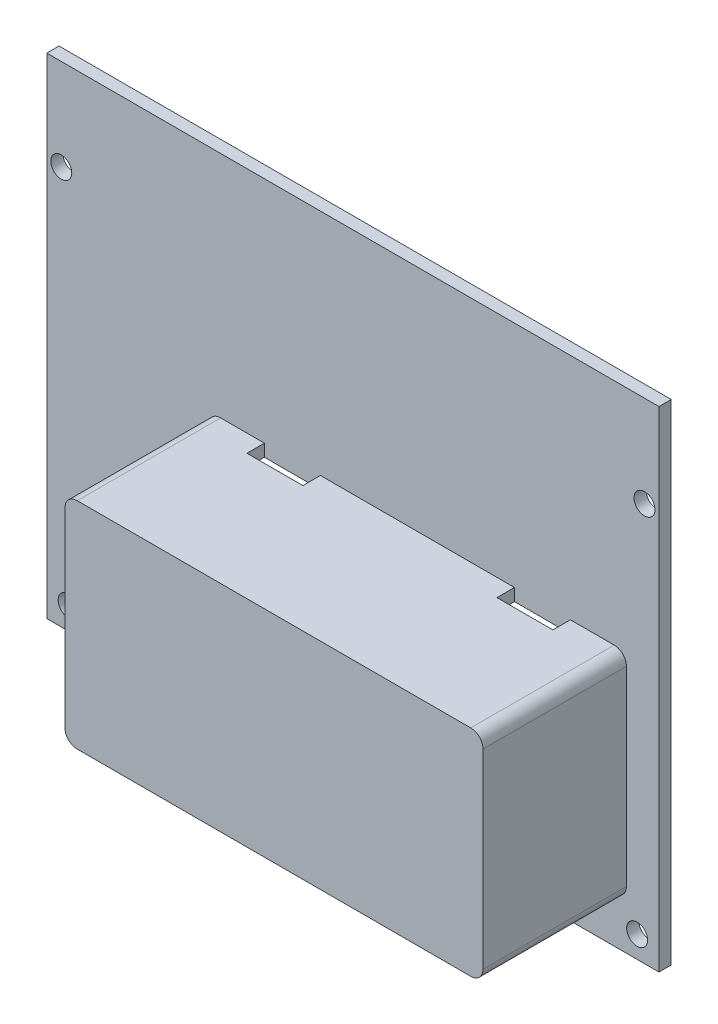
SolidWorks part; units mm, degrees
ref_plane "Front Plane" through (0, 0, 0) normal (0, 0, 1) x (1, 0, 0)
ref_plane "Top Plane" through (0, 0, 0) normal (0, 1, 0) x (1, 0, 0)
ref_plane "Right Plane" through (0, 0, 0) normal (1, 0, 0) x (0, 0, -1)
sketch "Sketch1" plane through (0, 0, 0) normal (0, 0, 1) x (1, 0, 0)
  line L1 (-44.45, 35.56) -> (44.45, 35.56)
  line L2 (-44.45, 35.56) -> (-44.45, -35.56)
  line L3 (-44.45, -35.56) -> (44.45, -35.56)
  line L4 (44.45, 35.56) -> (44.45, -35.56)
  line L5 (-44.45, 35.56) -> (44.45, -35.56) construction
  line L6 (-44.45, -35.56) -> (44.45, 35.56) construction
  point P0 (0, 0)
  dimension "D1" = 71.12
  dimension "D2" = 88.9
extrude "Boss-Extrude1" add sketch "Sketch1" along normal blind 1.778
sketch "Sketch2" plane through (0, 0, 0) normal (0, 0, -1) x (-1, 0, 0)
  circle A0 centre (-42.345, 22.2783) radius 1.524
  circle A1 centre (42.345, 22.2783) radius 1.524
  circle A2 centre (41.275, -32.385) radius 1.524
  circle A3 centre (-41.275, -32.385) radius 1.524
  dimension "D1" = 3.048
extrude "Cut-Extrude1" cut sketch "Sketch2" against normal blind 2.54
sketch "Sketch3" plane through (0, 0, 1.778) normal (0, 0, 1) x (1, 0, 0)
  line L0 (-19.204, -1.2487) -> (-19.204, -25.3787)
  line L5 (-17.426, -27.1567) -> (36.168, -27.1567)
  line L6 (37.946, -1.2487) -> (37.946, -25.3787)
  line L7 (-17.426, 0.5293) -> (36.168, 0.5293)
  line L8 (-20.982, 0.5293) -> (-20.982, -27.1567)
  line L9 (-19.204, -28.9347) -> (37.946, -28.9347)
  line L10 (39.724, 0.5293) -> (39.724, -27.1567)
  line L11 (-19.204, 2.3073) -> (37.946, 2.3073)
  line L12 (-20.982, 2.3073) -> (-20.982, -28.9347) construction
  line L13 (-20.982, -28.9347) -> (39.724, -28.9347) construction
  line L14 (39.724, 2.3073) -> (39.724, -28.9347) construction
  line L15 (-20.982, 2.3073) -> (39.724, 2.3073) construction
  line L16 (-19.204, 0.5293) -> (-19.204, -27.1567) construction
  line L17 (-19.204, -27.1567) -> (37.946, -27.1567) construction
  line L18 (37.946, 0.5293) -> (37.946, -27.1567) construction
  line L19 (-19.204, 0.5293) -> (37.946, 0.5293) construction
  arc A0 (-20.982, -27.1567) -> (-19.204, -28.9347) centre (-19.204, -27.1567) ccw
  arc A1 (37.946, -28.9347) -> (39.724, -27.1567) centre (37.946, -27.1567) ccw
  arc A2 (39.724, 0.5293) -> (37.946, 2.3073) centre (37.946, 0.5293) ccw
  arc A3 (-20.982, 0.5293) -> (-19.204, 2.3073) centre (-19.204, 0.5293) cw
  arc A4 (-19.204, -25.3787) -> (-17.426, -27.1567) centre (-17.426, -25.3787) ccw
  arc A5 (36.168, -27.1567) -> (37.946, -25.3787) centre (36.168, -25.3787) ccw
  arc A6 (37.946, -1.2487) -> (36.168, 0.5293) centre (36.168, -1.2487) ccw
  arc A7 (-19.204, -1.2487) -> (-17.426, 0.5293) centre (-17.426, -1.2487) cw
  dimension "D3" = 1.778
  dimension "D1" = 57.15
  dimension "D2" = 1.778
extrude "Boss-Extrude2" add sketch "Sketch3" along normal blind 19.05
sketch "Sketch4" plane through (0, 0, 1.778) normal (0, 0, 1) x (1, 0, 0)
  line L1 (-17.426, 0.5293) -> (36.168, 0.5293)
  line L2 (-19.204, -1.2487) -> (-19.204, -25.3787)
  line L3 (-17.426, -27.1567) -> (36.168, -27.1567)
  line L4 (37.946, -1.2487) -> (37.946, -25.3787)
  arc A0 (-19.204, -25.3787) -> (-17.426, -27.1567) centre (-17.426, -25.3787) ccw
  arc A1 (36.168, -27.1567) -> (37.946, -25.3787) centre (36.168, -25.3787) ccw
  arc A2 (36.168, 0.5293) -> (37.946, -1.2487) centre (36.168, -1.2487) cw
  arc A3 (-17.426, 0.5293) -> (-19.204, -1.2487) centre (-17.426, -1.2487) ccw
  point P13 (-19.204, 0.5293)
  dimension "D1" = 1.778
extrude "Cut-Extrude2" cut sketch "Sketch4" against normal blind 1.778
sketch "Sketch5" plane through (0, 0, 1.778) normal (0, 0, 1) x (1, 0, 0)
  line L0 (37.946, 2.3073) -> (-19.204, 2.3073) construction
  line L1 (9.371, 2.3073) -> (9.371, 12.4648) construction
  line L2 (-12.8453, 2.3073) -> (-4.7173, 2.3073)
  line L3 (31.5873, 2.3073) -> (23.4593, 2.3073)
  line L4 (-19.204, -28.9347) -> (37.946, -28.9347) construction
  line L5 (5.307, -28.9347) -> (13.435, -28.9347)
  arc A0 (-4.7173, 2.3073) -> (-12.8453, 2.3073) centre (-8.7813, 2.3073) ccw
  arc A1 (23.4593, 2.3073) -> (31.5873, 2.3073) centre (27.5233, 2.3073) cw
  arc A2 (5.307, -28.9347) -> (13.435, -28.9347) centre (9.371, -28.9347) ccw
  point P15 (9.371, -28.9347)
extrude "Boss-Extrude3" add sketch "Sketch5" along normal blind 2.54
sketch "Sketch6" plane through (0, 0, 4.318) normal (0, 0, 1) x (1, 0, 0)
  line L0 (5.307, -28.9347) -> (13.435, -28.9347)
  arc A0 (5.307, -28.9347) -> (13.435, -28.9347) centre (9.371, -28.9347) ccw
extrude "Boss-Extrude4" add sketch "Sketch6" along normal blind 3.81
sketch "Sketch7" plane through (0, 0, 20.828) normal (0, 0, 1) x (1, 0, 0)
  line L1 (-19.204, 2.3073) -> (37.946, 2.3073)
  line L2 (-20.982, 0.5293) -> (-20.982, -27.1567)
  line L3 (-19.204, -28.9347) -> (37.946, -28.9347)
  line L4 (39.724, 0.5293) -> (39.724, -27.1567)
  arc A0 (-20.982, -27.1567) -> (-19.204, -28.9347) centre (-19.204, -27.1567) ccw
  arc A1 (37.946, -28.9347) -> (39.724, -27.1567) centre (37.946, -27.1567) ccw
  arc A2 (37.946, 2.3073) -> (39.724, 0.5293) centre (37.946, 0.5293) cw
  arc A3 (-19.204, 2.3073) -> (-20.982, 0.5293) centre (-19.204, 0.5293) ccw
  dimension "D1" = 1.778
extrude "Boss-Extrude5" add sketch "Sketch7" along normal blind 1.778
sketch "Sketch10" plane through (-20.982, 0, 0) normal (-1, 0, 0) x (0, 0, 1)
  line L0 (1.778, 35.56) -> (1.778, -35.56) construction
  line L1 (1.778, -18.2667) -> (20.828, -18.2667)
  line L2 (1.778, -18.2667) -> (1.778, -8.3607)
  line L3 (1.778, -8.3607) -> (20.828, -8.3607)
  line L4 (20.828, -18.2667) -> (20.828, -8.3607)
  line L5 (20.828, -1.2487) -> (20.828, -25.3787) construction
  line L6 (22.606, -27.1567) -> (1.778, -27.1567) construction
  line L7 (22.606, 0.5293) -> (1.778, 0.5293) construction
  dimension "D1" = 8.89
  dimension "D2" = 8.89
extrude "Cut-Extrude5" cut sketch "Sketch10" against normal blind 1.778
sketch "Sketch12" plane through (0, 2.3073, 0) normal (0, 1, 0) x (1, 0, 0)
  line L1 (-12.8453, -1.778) -> (-4.7173, -1.778)
  line L2 (-12.8453, -1.778) -> (-12.8453, -4.318)
  line L3 (-12.8453, -4.318) -> (-4.7173, -4.318)
  line L4 (-4.7173, -1.778) -> (-4.7173, -4.318)
  line L5 (23.4593, -1.778) -> (31.5873, -1.778)
  line L6 (23.4593, -1.778) -> (23.4593, -4.318)
  line L7 (23.4593, -4.318) -> (31.5873, -4.318)
  line L8 (31.5873, -1.778) -> (31.5873, -4.318)
extrude "Cut-Extrude6" cut sketch "Sketch12" against normal mid plane 17.018
sketch "Sketch14" plane through (0, 0, 0) normal (0, 0, -1) x (-1, 0, 0)
  circle A0 centre (-9.371, -29.8247) radius 1.27
  dimension "D1" = 2.54
extrude "Cut-Extrude7" cut sketch "Sketch14" against normal blind 3.81
